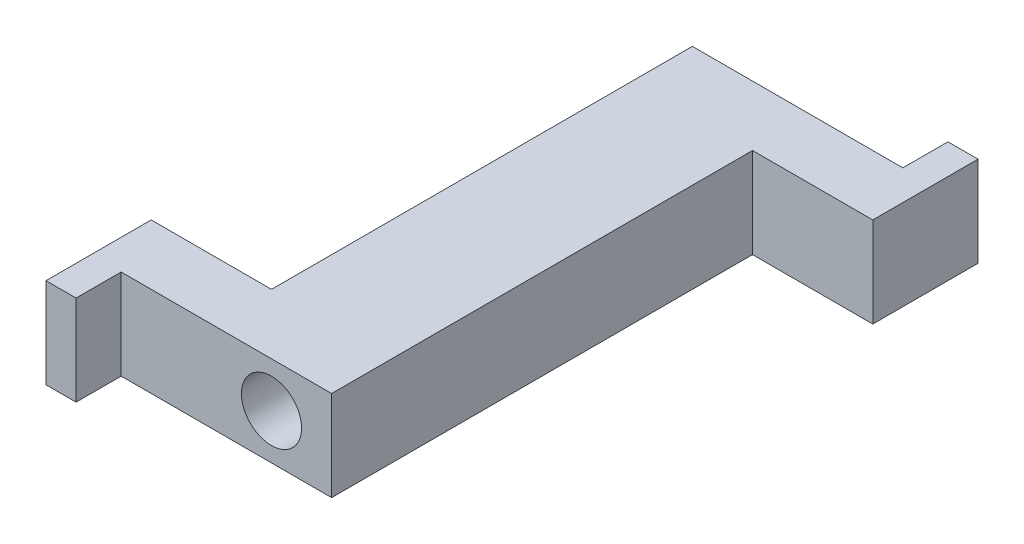
SolidWorks part; units mm, degrees
ref_plane "Front Plane" through (0, 0, 0) normal (0, 0, 1) x (1, 0, 0)
ref_plane "Top Plane" through (0, 0, 0) normal (0, 1, 0) x (1, 0, 0)
ref_plane "Right Plane" through (0, 0, 0) normal (1, 0, 0) x (0, 0, -1)
sketch "Sketch1" plane through (0, 0, 0) normal (0, 0, 1) x (1, 0, 0)
  line L1 (0, 0) -> (-25.4, 0)
  line L2 (0, 0) -> (0, 19.05)
  line L3 (0, 19.05) -> (-25.4, 19.05)
  line L4 (-25.4, 0) -> (-25.4, 19.05)
  dimension "D1" = 25.4
  dimension "D2" = 19.05
extrude "Boss-Extrude1" add sketch "Sketch1" along normal blind 101.6 contours L4 L3 L2 L1
sketch "Sketch2" plane through (0, 0, 101.6) normal (0, 0, 1) x (1, 0, 0)
  line L0 (-25.4, 19.05) -> (0, 0) construction
  circle A0 centre (-12.7, 9.525) radius 6.35
  dimension "D1" = 12.7
extrude "Cut-Extrude1" cut sketch "Sketch2" against normal blind 101.6
sketch "Sketch3" plane through (0, 19.05, 0) normal (0, 1, 0) x (1, 0, 0)
  line L5 (-25.4, -101.6) -> (-50.8, -101.6)
  line L6 (-25.4, -101.6) -> (-25.4, -88.9)
  line L7 (-25.4, -88.9) -> (-50.8, -88.9)
  line L8 (-50.8, -101.6) -> (-50.8, -88.9)
  dimension "D3" = 12.7
  dimension "D4" = 25.4
extrude "Boss-Extrude2" add sketch "Sketch3" against normal up to surface (19.05 mm away) up to face at (-12.7, 0, 50.8)
sketch "Sketch5" plane through (0, 0, 101.6) normal (0, 0, 1) x (1, 0, 0)
  line L0 (-50.8, 0) -> (-50.8, 19.05) construction
  line L1 (-50.8, 0) -> (-44.45, 0)
  line L2 (-50.8, 0) -> (-50.8, 19.05)
  line L3 (-50.8, 19.05) -> (-44.45, 19.05)
  line L4 (-44.45, 0) -> (-44.45, 19.05)
  line L5 (0, 19.05) -> (-50.8, 19.05) construction
  dimension "D1" = 6.35
extrude "Boss-Extrude4" add sketch "Sketch5" along normal blind 9.525
sketch "Sketch8" plane through (0, 19.05, 0) normal (0, 1, 0) x (1, 0, 0)
  line L1 (0, 0) -> (25.4, 0)
  line L2 (0, 0) -> (0, -12.7)
  line L3 (0, -12.7) -> (25.4, -12.7)
  line L4 (25.4, 0) -> (25.4, -12.7)
  dimension "D1" = 25.4
  dimension "D2" = 12.7
extrude "Boss-Extrude5" add sketch "Sketch8" against normal up to vertex (19.05 mm away) contours L1 L4 L3 L2
sketch "Sketch9" plane through (0, 0, 0) normal (0, 0, -1) x (-1, 0, 0)
  line L0 (-25.4, 0) -> (25.4, 0) construction
  line L1 (-25.4, 19.05) -> (-19.05, 19.05)
  line L2 (-25.4, 19.05) -> (-25.4, 0)
  line L3 (-25.4, 0) -> (-19.05, 0)
  line L4 (-19.05, 19.05) -> (-19.05, 0)
  dimension "D1" = 6.35
extrude "Boss-Extrude6" add sketch "Sketch9" along normal blind 9.525 contours L4 L3 L2 L1
